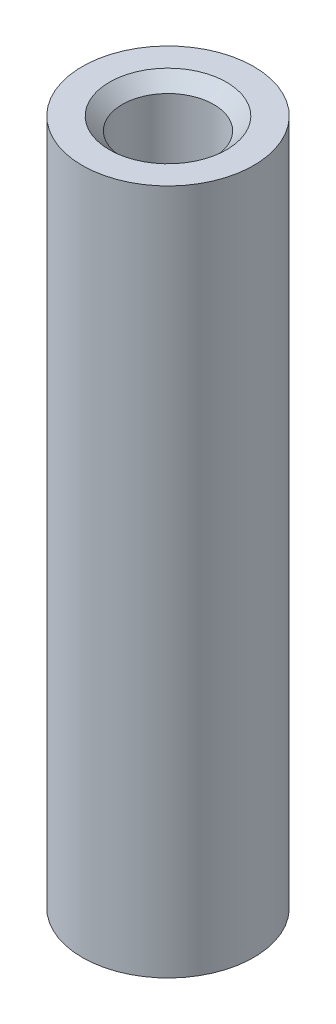
SolidWorks part; units mm, degrees
ref_plane "前视基准面" through (0, 0, 0) normal (0, 0, 1) x (1, 0, 0)
ref_plane "上视基准面" through (0, 0, 0) normal (0, 1, 0) x (1, 0, 0)
ref_plane "右视基准面" through (0, 0, 0) normal (1, 0, 0) x (0, 0, -1)
other "Configuration Table"
sketch "草图1" plane through (0, 0, 0) normal (0, 1, 0) x (1, 0, 0)
  circle A0 centre (0, 0) radius 1.5
  dimension "D1" = 3
extrude "凸台-拉伸1" add sketch "草图1" along normal blind 12
hole_wizard "M2 螺纹孔1" positions "草图2" profile "草图3" tap size "M2" standard "GB"
sketch "草图2" plane through (0, 12, 0) normal (0, 1, 0) x (1, 0, 0)
  point P0 (0, 0)
sketch "草图3" plane through (0, 12, 0) normal (1, 0, 0) x (0, 0, 1)
  line L0 (0, 0) -> (0, 16.4807)
  line L1 (0, 16.4807) -> (0.8, 16)
  line L2 (0.8, 16) -> (0.8, 0.225)
  line L3 (0.8, 0.225) -> (1.025, 0)
  line L5 (1.025, 0) -> (0, 0)
  line L6 (-0.8, 0.225) -> (-1.025, 0) construction
  line L10 (0, 16.4807) -> (-0.8, 16) construction
  line L11 (0, -6.35) -> (0, 107.95) construction
  dimension "螺纹孔钻头直径" = 1.6
  dimension "螺纹孔钻头深度" = 16
  dimension "近端锥形沉头孔直径" = 2.05
  dimension "近端锥形沉头孔角度" = 90
  dimension "导头角度" = 118
cosmetic thread "孔螺蚊线1"
